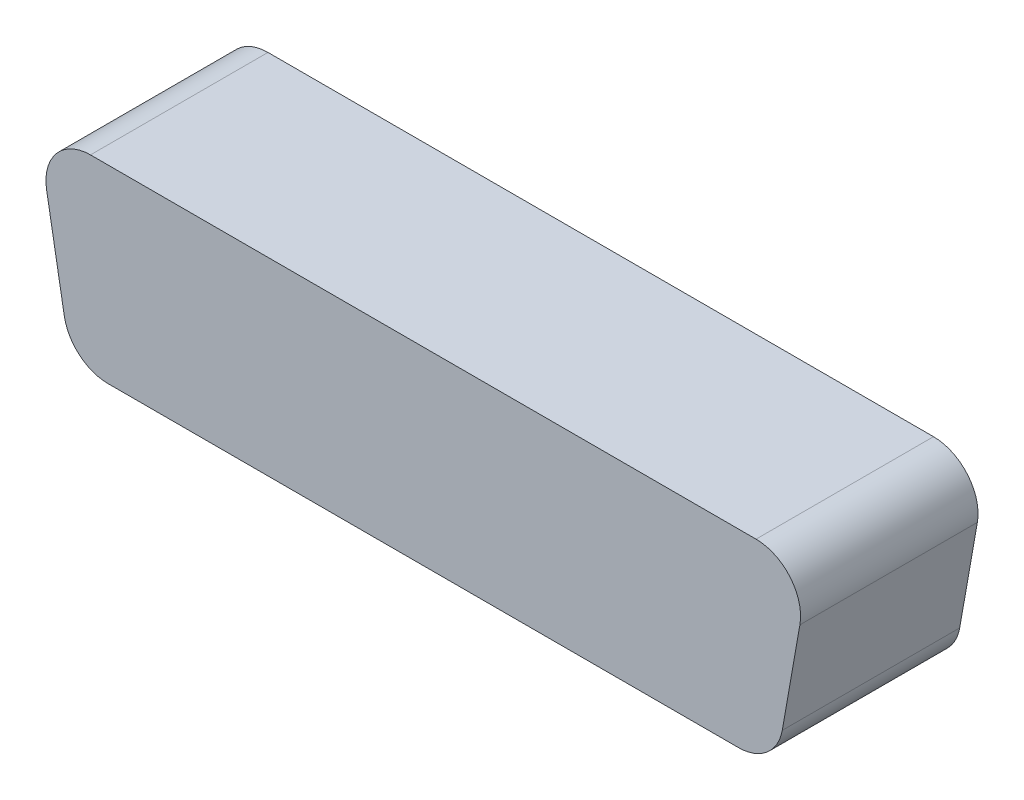
SolidWorks part; units mm, degrees
material "PBT General Purpose"
ref_plane "Ground_Plane" through (0, 0, 0) normal (0, 0, 1) x (1, 0, 0)
ref_plane "VehicleCentre_Plane" through (0, 0, 0) normal (0, 1, 0) x (1, 0, 0)
ref_plane "FrontAxle_Plane" through (0, 0, 0) normal (1, 0, 0) x (0, 0, -1)
sketch "Sketch1" plane through (0, 0, 0) normal (0, 0, 1) x (1, 0, 0)
  line L0 (-18.7505, 10.668) -> (18.7505, 10.668)
  line L1 (21.2224, 7.7221) -> (20.2265, 2.0741)
  line L2 (17.7546, 0) -> (-17.7546, 0)
  line L3 (-20.2265, 2.0741) -> (-21.2224, 7.7221)
  arc A0 (-18.7505, 10.668) -> (-21.2224, 7.7221) centre (-18.7505, 8.158) ccw
  arc A1 (21.2224, 7.7221) -> (18.7505, 10.668) centre (18.7505, 8.158) ccw
  arc A2 (17.7546, 0) -> (20.2265, 2.0741) centre (17.7546, 2.51) ccw
  arc A3 (-20.2265, 2.0741) -> (-17.7546, 0) centre (-17.7546, 2.51) ccw
  point P16 (20.4074, 0)
  point P17 (0, 0)
  dimension "D3" = 5.02
  dimension "D1" = 35.5092
  dimension "D4" = 100
  dimension "D5" = 10.668
extrude "Boss-Extrude1" add sketch "Sketch1" along normal blind 10
